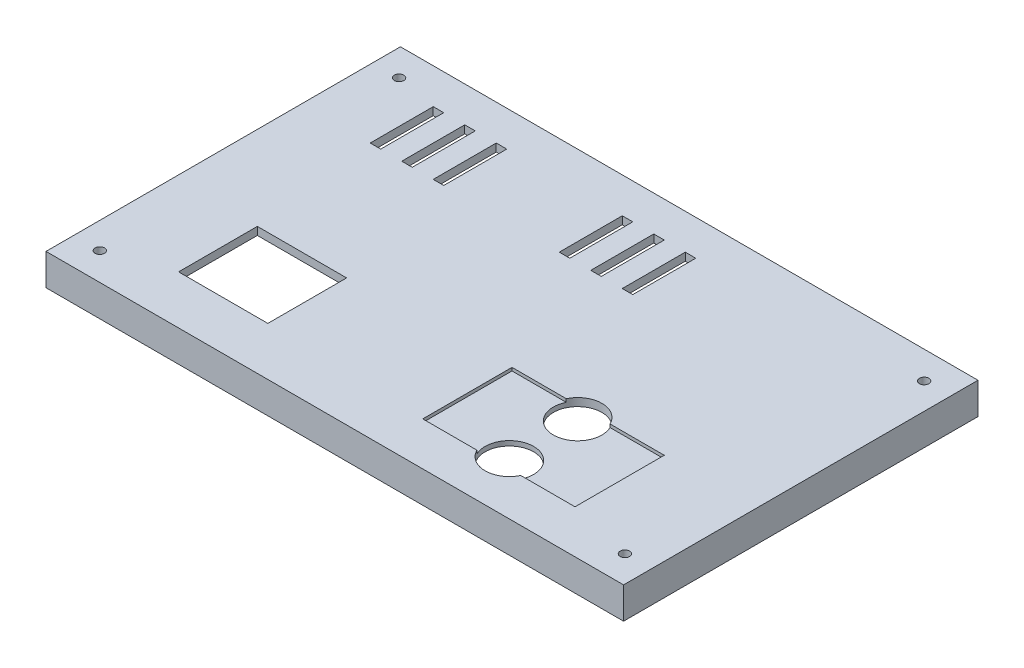
SolidWorks part; units mm, degrees
ref_plane "前视基准面" through (0, 0, 0) normal (0, 0, 1) x (1, 0, 0)
ref_plane "上视基准面" through (0, 0, 0) normal (0, 1, 0) x (1, 0, 0)
ref_plane "右视基准面" through (0, 0, 0) normal (1, 0, 0) x (0, 0, -1)
other "Configuration Table"
sketch "草图1" plane through (0, 0, 0) normal (0, 1, 0) x (1, 0, 0)
  line L1 (-110, -67.5) -> (110, -67.5)
  line L2 (-110, -67.5) -> (-110, 67.5)
  line L3 (-110, 67.5) -> (110, 67.5)
  line L4 (110, -67.5) -> (110, 67.5)
extrude "Lid_Top_3mm" add sketch "草图1" against normal blind 3
sketch "草图2" plane through (0, 0, 0) normal (0, 1, 0) x (1, 0, 0)
  line L0 (110, 67.5) -> (-110, 67.5) construction
  line L1 (-108, 65.5) -> (108, 65.5)
  line L2 (-108, 65.5) -> (-108, 67.5)
  line L3 (-108, 67.5) -> (108, 67.5)
  line L4 (108, 65.5) -> (108, 67.5)
extrude "Lid_Rim_Back" add sketch "草图2" against normal blind 12
sketch "草图3" plane through (0, 0, 0) normal (0, 1, 0) x (1, 0, 0)
  line L0 (-110, -67.5) -> (110, -67.5) construction
  line L1 (-108, -67.5) -> (108, -67.5)
  line L2 (-108, -67.5) -> (-108, -65.5)
  line L3 (-108, -65.5) -> (108, -65.5)
  line L4 (108, -67.5) -> (108, -65.5)
extrude "Lid_Rim_Front" add sketch "草图3" against normal blind 12
sketch "草图4" plane through (0, 0, 0) normal (0, 1, 0) x (1, 0, 0)
  line L1 (-110, -67.5) -> (-108, -67.5)
  line L2 (-110, -67.5) -> (-110, 67.5)
  line L3 (-110, 67.5) -> (-108, 67.5)
  line L4 (-108, -67.5) -> (-108, 67.5)
extrude "Lid_Rim_Left" add sketch "草图4" against normal blind 12
sketch "草图5" plane through (0, 0, 0) normal (0, 1, 0) x (1, 0, 0)
  line L0 (-110, -67.5) -> (110, -67.5) construction
  line L1 (108, -67.5) -> (110, -67.5)
  line L2 (108, -67.5) -> (108, 67.5)
  line L3 (108, 67.5) -> (110, 67.5)
  line L4 (110, -67.5) -> (110, 67.5)
extrude "Lid_Rim_Right" add sketch "草图5" against normal blind 12
sketch "草图6" plane through (0, 0, 0) normal (0, 1, 0) x (1, 0, 0)
  circle A0 centre (-100, -57) radius 1.8
extrude "Lid_Screw_Clearance_1" cut sketch "草图6" against normal blind 16
sketch "草图7" plane through (0, 0, 0) normal (0, 1, 0) x (1, 0, 0)
  circle A0 centre (100, -57) radius 1.8
extrude "Lid_Screw_Clearance_2" cut sketch "草图7" against normal blind 16
sketch "草图8" plane through (0, 0, 0) normal (0, 1, 0) x (1, 0, 0)
  circle A0 centre (-100, 57) radius 1.8
extrude "Lid_Screw_Clearance_3" cut sketch "草图8" against normal blind 16
sketch "草图9" plane through (0, 0, 0) normal (0, 1, 0) x (1, 0, 0)
  circle A0 centre (100, 57) radius 1.8
extrude "Lid_Screw_Clearance_4" cut sketch "草图9" against normal blind 16
sketch "草图10" plane through (0, 0, 0) normal (0, 1, 0) x (1, 0, 0)
  circle A0 centre (-61, -34) radius 9
extrude "OV5647_Lens_Opening_D18" cut sketch "草图10" against normal blind 4
sketch "草图11" plane through (0, 0, 0) normal (0, 1, 0) x (1, 0, 0)
  line L1 (-78, -49) -> (-44, -49)
  line L2 (-78, -49) -> (-78, -19)
  line L3 (-78, -19) -> (-44, -19)
  line L4 (-44, -49) -> (-44, -19)
extrude "OV5647_Service_Clearance" cut sketch "草图11" against normal blind 4
sketch "草图12" plane through (0, 0, 0) normal (0, 1, 0) x (1, 0, 0)
  circle A0 centre (46, -47) radius 9.25
extrude "HC_SR04_Acoustic_Opening_1" cut sketch "草图12" against normal blind 4
sketch "草图13" plane through (0, 0, 0) normal (0, 1, 0) x (1, 0, 0)
  circle A0 centre (46, -21) radius 9.25
extrude "HC_SR04_Acoustic_Opening_2" cut sketch "草图13" against normal blind 4
sketch "草图14" plane through (0, 0, 0) normal (0, 1, 0) x (1, 0, 0)
  line L1 (17, -51) -> (75, -51)
  line L2 (17, -51) -> (17, -17)
  line L3 (17, -17) -> (75, -17)
  line L4 (75, -51) -> (75, -17)
extrude "HC_SR04_Recess" cut sketch "草图14" against normal blind 1.2
sketch "草图15" plane through (0, 0, 0) normal (0, 1, 0) x (1, 0, 0)
  line L1 (-84, 30) -> (-80, 30)
  line L2 (-84, 30) -> (-84, 54)
  line L3 (-84, 54) -> (-80, 54)
  line L4 (-80, 30) -> (-80, 54)
extrude "Vent_Slot_1" cut sketch "草图15" against normal blind 4
sketch "草图16" plane through (0, 0, 0) normal (0, 1, 0) x (1, 0, 0)
  line L1 (-72, 30) -> (-68, 30)
  line L2 (-72, 30) -> (-72, 54)
  line L3 (-72, 54) -> (-68, 54)
  line L4 (-68, 30) -> (-68, 54)
extrude "Vent_Slot_2" cut sketch "草图16" against normal blind 4
sketch "草图17" plane through (0, 0, 0) normal (0, 1, 0) x (1, 0, 0)
  line L1 (-60, 30) -> (-56, 30)
  line L2 (-60, 30) -> (-60, 54)
  line L3 (-60, 54) -> (-56, 54)
  line L4 (-56, 30) -> (-56, 54)
extrude "Vent_Slot_3" cut sketch "草图17" against normal blind 4
sketch "草图18" plane through (0, 0, 0) normal (0, 1, 0) x (1, 0, 0)
  line L1 (-12, 30) -> (-8, 30)
  line L2 (-12, 30) -> (-12, 54)
  line L3 (-12, 54) -> (-8, 54)
  line L4 (-8, 30) -> (-8, 54)
extrude "Vent_Slot_4" cut sketch "草图18" against normal blind 4
sketch "草图19" plane through (0, 0, 0) normal (0, 1, 0) x (1, 0, 0)
  line L1 (0, 30) -> (4, 30)
  line L2 (0, 30) -> (0, 54)
  line L3 (0, 54) -> (4, 54)
  line L4 (4, 30) -> (4, 54)
extrude "Vent_Slot_5" cut sketch "草图19" against normal blind 4
sketch "草图20" plane through (0, 0, 0) normal (0, 1, 0) x (1, 0, 0)
  line L1 (12, 30) -> (16, 30)
  line L2 (12, 30) -> (12, 54)
  line L3 (12, 54) -> (16, 54)
  line L4 (16, 30) -> (16, 54)
extrude "Vent_Slot_6" cut sketch "草图20" against normal blind 4
